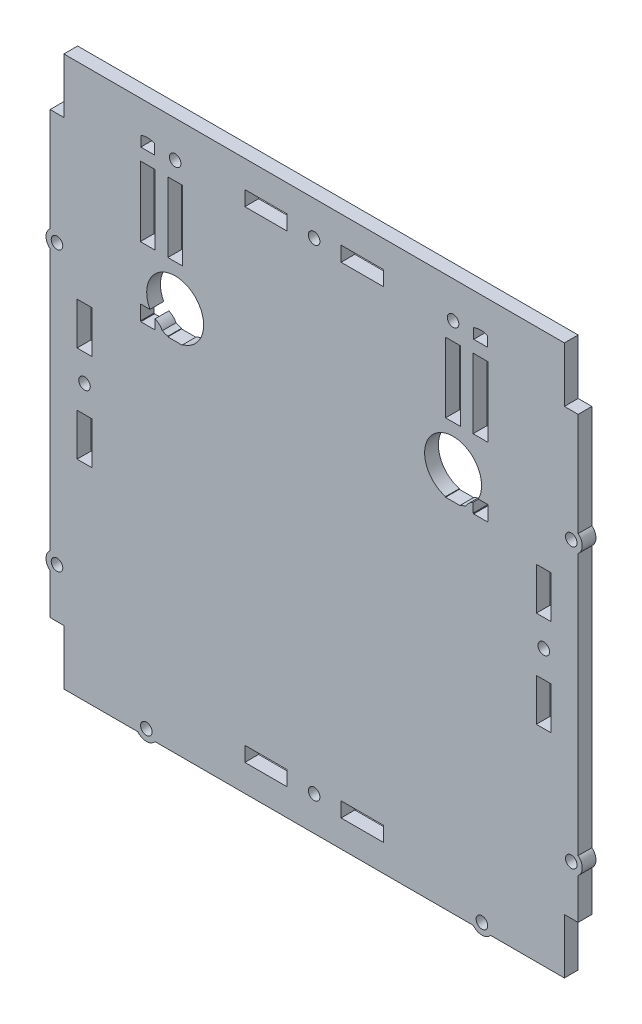
SolidWorks part; units mm, degrees
ref_plane "Front Plane" through (0, 0, 0) normal (0, 0, 1) x (1, 0, 0)
ref_plane "Top Plane" through (0, 0, 0) normal (0, 1, 0) x (1, 0, 0)
ref_plane "Right Plane" through (0, 0, 0) normal (1, 0, 0) x (0, 0, -1)
sketch "Sketch1" plane through (0, 0, 0) normal (0, 0, 1) x (1, 0, 0)
  line L0 (-182, 200) -> (-182, 180)
  line L1 (-182, 180) -> (-187, 180)
  line L2 (-187, 180) -> (-187, 20)
  line L3 (-187, 20) -> (-182, 20)
  line L4 (-182, 20) -> (-182, 0)
  line L5 (-182, 0) -> (0, 0)
  line L6 (0, 0) -> (0, 20)
  line L7 (0, 20) -> (5, 20)
  line L8 (5, 20) -> (5, 180)
  line L9 (5, 180) -> (0, 180)
  line L10 (0, 180) -> (0, 200)
  line L11 (0, 200) -> (-182, 200)
  dimension "D1" = 182
  dimension "D2" = 160
  dimension "D3" = 20
  dimension "D4" = 20
  dimension "D5" = 5
  dimension "D6" = 5
  dimension "D7" = 5
  dimension "D8" = 5
  dimension "D9" = 20
  dimension "D10" = 20
extrude "Boss-Extrude1" add sketch "Sketch1" along normal blind 5
sketch "Sketch2" plane through (0, 0, 0) normal (0, 0, -1) x (-1, 0, 0)
  line L0 (0, 200) -> (182, 200) construction
  line L1 (-5, 20) -> (-5, 180) construction
  line L3 (182, 0) -> (0, 0) construction
  line L4 (91, 200) -> (91, 0) construction
  circle A0 centre (-2.5, 139.3) radius 2.1
  circle A1 centre (-2.5, 37.9) radius 2.1
  circle A2 centre (184.5, 37.9) radius 2.1
  circle A3 centre (184.5, 139.3) radius 2.1
  dimension "D1" = 4.2
  dimension "D3" = 2.5
  dimension "D4" = 4.2
  dimension "D5" = 2.5
  dimension "D6" = 37.9
  dimension "D2" = 60.7
extrude "Cut-Extrude1" cut sketch "Sketch2" against normal blind 10
sketch "Sketch3" plane through (0, 0, 0) normal (0, 0, -1) x (-1, 0, 0)
  line L0 (-5, 20) -> (-5, 180) construction
  line L1 (-5, 136.1775) -> (-5, 142.4225)
  arc A0 (-5, 142.4225) -> (-5, 136.1775) centre (-2.5, 139.3) ccw
  dimension "D1" = 8
extrude "Boss-Extrude2" add sketch "Sketch3" against normal blind 5
sketch "Sketch4" plane through (0, 0, 0) normal (0, 0, -1) x (-1, 0, 0)
  line L0 (-5, 20) -> (-5, 136.1775) construction
  line L1 (-5, 34.7775) -> (-5, 41.0225)
  arc A0 (-5, 41.0225) -> (-5, 34.7775) centre (-2.5, 37.9) ccw
extrude "Boss-Extrude3" add sketch "Sketch4" against normal blind 5
ref_plane "Plane1" through (-91, 0, 0) normal (-1, 0, 0) x (0, 0, 1)
mirror "Mirror1" about plane through (-91, 0, 0) normal (-1, 0, 0) of "Boss-Extrude2", "Boss-Extrude3"
sketch "Sketch5" plane through (0, 0, 0) normal (0, 0, -1) x (-1, 0, 0)
  line L0 (182, 0) -> (0, 0) construction
  line L1 (182, 20) -> (182, 0) construction
  line L2 (0, 0) -> (0, 20) construction
  circle A0 centre (30, 2.5) radius 2.1
  circle A1 centre (152, 2.5) radius 2.1
  dimension "D1" = 2.5
  dimension "D3" = 30
  dimension "D2" = 2.5
  dimension "D4" = 30
extrude "Cut-Extrude2" cut sketch "Sketch5" against normal blind 5
sketch "Sketch6" plane through (0, 0, 0) normal (0, 0, -1) x (-1, 0, 0)
  line L0 (182, 0) -> (0, 0) construction
  line L1 (155.1225, 0) -> (148.8775, 0)
  line L2 (33.1225, 0) -> (26.8775, 0)
  arc A0 (26.8775, 0) -> (33.1225, 0) centre (30, 2.5) ccw
  arc A1 (148.8775, 0) -> (155.1225, 0) centre (152, 2.5) ccw
extrude "Boss-Extrude4" add sketch "Sketch6" against normal blind 5
sketch "Sketch7" plane through (0, 0, 5) normal (0, 0, 1) x (1, 0, 0)
  line L2 (5, 142.4225) -> (5, 180) construction
  line L4 (-27.8, 154.8) -> (-33.2, 154.8)
  line L5 (-33.2, 154.8) -> (-33.2, 180.2)
  line L6 (-33.2, 180.2) -> (-27.8, 180.2)
  line L7 (-27.8, 154.8) -> (-27.8, 180.2)
  line L8 (-37.8, 154.8) -> (-37.8, 180.2)
  line L9 (-37.8, 180.2) -> (-43.2, 180.2)
  line L10 (-43.2, 180.2) -> (-43.2, 154.8)
  line L11 (-43.2, 154.8) -> (-37.8, 154.8)
  line L12 (0, 200) -> (-182, 200) construction
  line L13 (0, 200) -> (-182, 200) construction
  line L15 (-27.8, 129.8) -> (-33.2, 129.8)
  line L16 (-27.8, 129.8) -> (-27.8, 135.2)
  line L17 (-27.8, 135.2) -> (-33.2, 135.2)
  line L18 (-33.2, 129.8) -> (-33.2, 135.2)
  line L19 (-37.8, 129.8) -> (-43.2, 129.8)
  line L20 (-37.8, 129.8) -> (-37.8, 135.2)
  line L21 (-37.8, 135.2) -> (-43.2, 135.2)
  line L22 (-43.2, 129.8) -> (-43.2, 135.2)
  dimension "D1" = 5.4
  dimension "D2" = 4.6
  dimension "D3" = 5.4
  dimension "D4" = 25.4
  dimension "D5" = 19.8
  dimension "D6" = 5.4
  dimension "D7" = 5.4
  dimension "D8" = 5.4
  dimension "D9" = 5.4
  dimension "D10" = 19.6
  dimension "D11" = 32.8
extrude "Cut-Extrude4" cut sketch "Sketch7" against normal blind 5
mirror "Mirror2" about plane through (-91, 0, 0) normal (-1, 0, 0) of "Cut-Extrude4"
sketch "Sketch8" plane through (0, 0, 0) normal (0, 0, -1) x (-1, 0, 0)
  line L0 (81, 15) -> (66, 15) construction
  line L1 (66, 15) -> (66, 10) construction
  line L2 (66, 10) -> (81, 10) construction
  line L3 (81, 10) -> (81, 15) construction
  line L4 (116, 15) -> (101, 15) construction
  line L5 (101, 15) -> (101, 10) construction
  line L6 (101, 10) -> (116, 10) construction
  line L7 (116, 10) -> (116, 15) construction
  line L8 (81, 15) -> (66, 15)
  line L9 (66, 15) -> (66, 10)
  line L10 (66, 10) -> (81, 10)
  line L11 (81, 10) -> (81, 15)
  line L12 (116, 15) -> (101, 15)
  line L13 (101, 15) -> (101, 10)
  line L14 (101, 10) -> (116, 10)
  line L15 (116, 10) -> (116, 15)
  line L16 (172, 90) -> (172.0286, 110) construction
  line L17 (177, 90) -> (172, 90) construction
  line L18 (172, 75) -> (172, 90) construction
  line L19 (177, 110) -> (172, 110) construction
  line L20 (172.0143, 100) -> (55.2635, 100) construction
  line L21 (116.2, 190.2) -> (116.2, 184.8)
  line L22 (100.8, 190.2) -> (116.2, 190.2)
  line L23 (100.8, 184.8) -> (100.8, 190.2)
  line L24 (81.2, 15.2) -> (65.8, 15.2)
  line L25 (65.8, 15.2) -> (65.8, 9.8)
  line L26 (65.8, 9.8) -> (81.2, 9.8)
  line L27 (81.2, 9.8) -> (81.2, 15.2)
  line L28 (81.2, 15.2) -> (65.8, 15.2)
  line L29 (65.8, 15.2) -> (65.8, 9.8)
  line L30 (65.8, 9.8) -> (81.2, 9.8)
  line L31 (81.2, 9.8) -> (81.2, 15.2)
  line L32 (100.8, 12.5) -> (81.2, 12.5) construction
  line L33 (116.2, 184.8) -> (100.8, 184.8)
  line L34 (81.2, 190.2) -> (81.2, 184.8)
  line L35 (65.8, 190.2) -> (81.2, 190.2)
  line L36 (116.2, 15.2) -> (100.8, 15.2)
  line L37 (100.8, 15.2) -> (100.8, 9.8)
  line L38 (100.8, 9.8) -> (116.2, 9.8)
  line L39 (116.2, 9.8) -> (116.2, 15.2)
  line L40 (116.2, 15.2) -> (100.8, 15.2)
  line L41 (100.8, 15.2) -> (100.8, 9.8)
  line L42 (100.8, 9.8) -> (116.2, 9.8)
  line L43 (116.2, 9.8) -> (116.2, 15.2)
  line L44 (65.8, 184.8) -> (65.8, 190.2)
  line L45 (81.2, 184.8) -> (65.8, 184.8)
  line L46 (116, 190) -> (116, 185)
  line L47 (101, 190) -> (116, 190)
  line L48 (101, 185) -> (101, 190)
  line L49 (116, 185) -> (101, 185)
  line L50 (81, 190) -> (81, 185)
  line L51 (66, 190) -> (81, 190)
  line L52 (66, 185) -> (66, 190)
  line L53 (81, 185) -> (66, 185)
  line L54 (172, 125) -> (172, 110) construction
  line L55 (172, 110) -> (177, 110) construction
  line L56 (177, 110) -> (177, 125) construction
  line L57 (177, 125) -> (172, 125) construction
  line L58 (172, 90) -> (172, 75) construction
  line L59 (172, 75) -> (177, 75) construction
  line L60 (177, 75) -> (177, 90) construction
  line L61 (172, 125) -> (172, 110)
  line L62 (172, 110) -> (177, 110)
  line L63 (177, 110) -> (177, 125)
  line L64 (177, 125) -> (172, 125)
  line L65 (172, 90) -> (172, 75)
  line L66 (172, 75) -> (177, 75)
  line L67 (177, 75) -> (177, 90)
  line L68 (177, 90) -> (172, 90)
  line L69 (5, 125) -> (5, 110) construction
  line L70 (5, 110) -> (10, 110) construction
  line L71 (10, 110) -> (10, 125) construction
  line L72 (10, 125) -> (5, 125) construction
  line L73 (5, 90) -> (5, 75) construction
  line L74 (5, 75) -> (10, 75) construction
  line L75 (10, 75) -> (10, 90) construction
  line L76 (10, 90) -> (5, 90) construction
  line L77 (5, 125) -> (5, 110)
  line L78 (5, 110) -> (10, 110)
  line L79 (10, 110) -> (10, 125)
  line L80 (10, 125) -> (5, 125)
  line L81 (5, 90) -> (5, 75)
  line L82 (5, 75) -> (10, 75)
  line L83 (10, 75) -> (10, 90)
  line L84 (10, 90) -> (5, 90)
  line L93 (171.8, 90.2) -> (171.8, 74.8)
  line L94 (171.8, 74.8) -> (177.2, 74.8)
  line L95 (177.2, 74.8) -> (177.2, 90.2)
  line L96 (177.2, 90.2) -> (171.8, 90.2)
  line L97 (171.8, 90.2) -> (171.8, 74.8)
  line L98 (171.8, 74.8) -> (177.2, 74.8)
  line L99 (177.2, 74.8) -> (177.2, 90.2)
  line L100 (177.2, 90.2) -> (171.8, 90.2)
  line L105 (171.8, 125.2) -> (171.8, 109.8)
  line L106 (171.8, 109.8) -> (177.2, 109.8)
  line L107 (177.2, 109.8) -> (177.2, 125.2)
  line L108 (177.2, 125.2) -> (171.8, 125.2)
  line L109 (171.8, 125.2) -> (171.8, 109.8)
  line L110 (171.8, 109.8) -> (177.2, 109.8)
  line L111 (177.2, 109.8) -> (177.2, 125.2)
  line L112 (177.2, 125.2) -> (171.8, 125.2)
  line L117 (4.8, 90.2) -> (4.8, 74.8)
  line L118 (4.8, 74.8) -> (10.2, 74.8)
  line L119 (10.2, 74.8) -> (10.2, 90.2)
  line L120 (10.2, 90.2) -> (4.8, 90.2)
  line L121 (4.8, 90.2) -> (4.8, 74.8)
  line L122 (4.8, 74.8) -> (10.2, 74.8)
  line L123 (10.2, 74.8) -> (10.2, 90.2)
  line L124 (10.2, 90.2) -> (4.8, 90.2)
  line L125 (172.0143, 100) -> (176.9857, 100)
  line L126 (91, 12.5) -> (91, 40.5503) construction
  line L129 (4.8, 125.2) -> (4.8, 109.8)
  line L130 (4.8, 109.8) -> (10.2, 109.8)
  line L131 (10.2, 109.8) -> (10.2, 125.2)
  line L132 (10.2, 125.2) -> (4.8, 125.2)
  line L133 (4.8, 125.2) -> (4.8, 109.8)
  line L134 (4.8, 109.8) -> (10.2, 109.8)
  line L135 (10.2, 109.8) -> (10.2, 125.2)
  line L136 (10.2, 125.2) -> (4.8, 125.2)
  circle A0 centre (91, 12.5) radius 2.1
  circle A1 centre (91, 187.5) radius 2.1
  circle A2 centre (174.5, 100) radius 2.1
  circle A3 centre (7.5, 100) radius 2.1
  dimension "D3" = 4.2
  dimension "D8" = 4.2
  dimension "D9" = 2.5
  dimension "D1" = 0.2
  dimension "D2" = 0.2
  dimension "D4" = 0.2
  dimension "D5" = 0.2
  dimension "D6" = 0.2
  dimension "D7" = 0.2
extrude "Cut-Extrude5" cut sketch "Sketch8" against normal blind 5 contours L10 L11 L8 L9 | L30 L31 L28 L29 | A0 | L40 L41 L42 L43 | L100 L97 L98 L99 | A2 | L110 L111 L112 L109 | L22 L21 L33 L23 | A1 | L34 L45 L44 L35 | L134 L135 L136 L133 | A3 | L124 L121 L122 L123
sketch "Sketch9" plane through (0, 0, 5) normal (0, 0, 1) x (1, 0, 0)
  line L4 (-81, 10) -> (-66, 10)
  line L5 (-66, 10) -> (-66, 15)
  line L6 (-66, 15) -> (-81, 15)
  line L7 (-81, 15) -> (-81, 10)
  line L8 (-81, 10) -> (-66, 10)
  line L9 (-66, 10) -> (-66, 15)
  line L10 (-66, 15) -> (-81, 15)
  line L11 (-81, 15) -> (-81, 10)
  dimension "D1" = 0
extrude "Cut-Extrude6" cut sketch "Sketch9" against normal blind 10
sketch "Sketch10" plane through (0, 0, 5) normal (0, 0, 1) x (1, 0, 0)
  line L0 (-149.03, 133.8471) -> (-149.03, 129.6471) construction
  line L1 (-149.03, 129.6471) -> (-154.03, 129.6471) construction
  line L2 (-154.03, 129.6471) -> (-154.03, 133.8471) construction
  line L3 (-154.03, 133.8471) -> (-149.03, 133.8471) construction
  line L4 (-144.03, 129.6472) -> (-144.03, 133.8472) construction
  line L5 (-144.03, 133.8472) -> (-139.03, 133.8472) construction
  line L6 (-139.03, 133.8472) -> (-139.03, 129.6472) construction
  line L7 (-139.03, 129.6472) -> (-144.03, 129.6472) construction
  line L8 (-144.0301, 184.6472) -> (-144.0301, 188.8472) construction
  line L9 (-144.0301, 188.8472) -> (-139.0301, 188.8472) construction
  line L10 (-139.0301, 188.8472) -> (-139.0301, 184.6472) construction
  line L11 (-139.0301, 184.6472) -> (-144.0301, 184.6472) construction
  line L12 (-149.0301, 188.8471) -> (-149.0301, 184.6471) construction
  line L13 (-149.0301, 184.6471) -> (-154.0301, 184.6471) construction
  line L14 (-154.0301, 184.6471) -> (-154.0301, 188.8471) construction
  line L15 (-154.0301, 188.8471) -> (-149.0301, 188.8471) construction
  line L16 (-149.03, 133.8471) -> (-149.03, 129.6471)
  line L17 (-149.03, 129.6471) -> (-154.03, 129.6471)
  line L18 (-154.03, 129.6471) -> (-154.03, 133.8471)
  line L19 (-154.03, 133.8471) -> (-149.03, 133.8471)
  line L20 (-144.03, 129.6472) -> (-144.03, 133.8472)
  line L21 (-144.03, 133.8472) -> (-139.03, 133.8472)
  line L22 (-139.03, 133.8472) -> (-139.03, 129.6472)
  line L23 (-139.03, 129.6472) -> (-144.03, 129.6472)
  line L24 (-144.0301, 184.6472) -> (-144.0301, 188.8472)
  line L25 (-144.0301, 188.8472) -> (-139.0301, 188.8472)
  line L26 (-139.0301, 188.8472) -> (-139.0301, 184.6472)
  line L27 (-139.0301, 184.6472) -> (-144.0301, 184.6472)
  line L28 (-149.0301, 188.8471) -> (-149.0301, 184.6471)
  line L29 (-149.0301, 184.6471) -> (-154.0301, 184.6471)
  line L30 (-154.0301, 184.6471) -> (-154.0301, 188.8471)
  line L31 (-154.0301, 188.8471) -> (-149.0301, 188.8471)
  circle A0 centre (-141.53, 186.7472) radius 2.1
  circle A1 centre (-151.53, 182.6942) radius 6.1529
  circle A2 centre (-141.53, 140) radius 10.3528
  circle A3 centre (-151.53, 127.6942) radius 6.1529
  dimension "D1" = 4.2
extrude "Cut-Extrude7" cut sketch "Sketch10" against normal blind 10 contours A0 | A1 | A2 | A3
ref_plane "Plane2" through (-91, 0, 0) normal (1, 0, 0) x (0, 0, -1)
mirror "Mirror3" about plane through (-91, 0, 0) normal (1, 0, 0) of "Cut-Extrude7"
